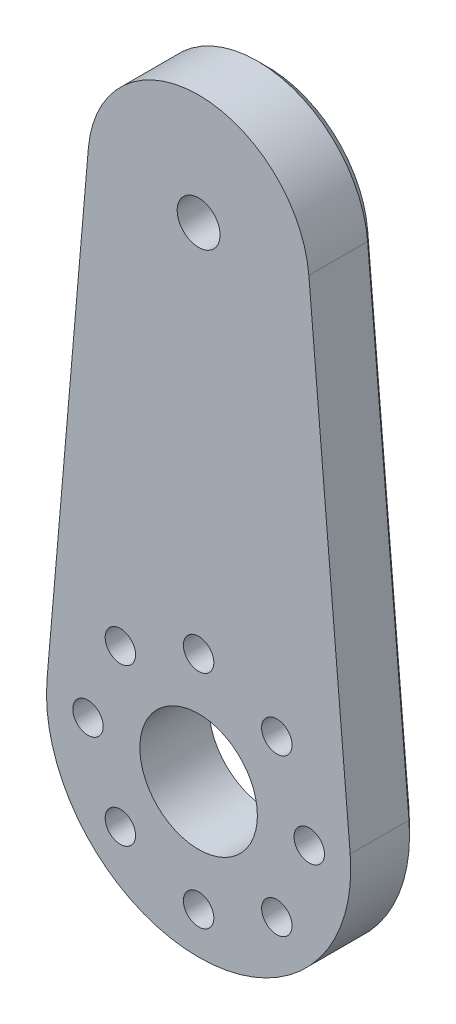
SolidWorks part; units mm, degrees
ref_plane "Front Plane" through (0, 0, 0) normal (0, 0, 1) x (1, 0, 0)
ref_plane "Top Plane" through (0, 0, 0) normal (0, 1, 0) x (1, 0, 0)
ref_plane "Right Plane" through (0, 0, 0) normal (1, 0, 0) x (0, 0, -1)
sketch "Sketch1" plane through (0, 0, 0) normal (0, 0, 1) x (1, 0, 0)
  line L0 (-23.0882, 16.319) -> (-26.0771, -18.4239)
  line L3 (-7.1471, 16.319) -> (-4.1581, -18.4239)
  line L4 (-15.1176, 0.8298) -> (-15.1176, 20.8298) construction
  line L5 (-14.7664, -19.3668) -> (49985.2336, -19.3668) construction
  circle A2 centre (-15.1176, 15.6332) radius 1.55
  circle A3 centre (-15.1176, -19.3668) radius 4.25
  arc A5 (-7.1471, 16.319) -> (-23.0882, 16.319) centre (-15.1176, 15.6332) ccw
  arc A6 (-26.0771, -18.4239) -> (-4.1581, -18.4239) centre (-15.1176, -19.3668) ccw
  circle A7 centre (-15.0314, -20.0888) radius 11 construction
  circle A8 centre (-7.1176, -19.3668) radius 1.1
  circle A9 centre (-9.4608, -25.0236) radius 1.1
  circle A10 centre (-15.1176, -27.3668) radius 1.1
  circle A11 centre (-20.7745, -25.0236) radius 1.1
  circle A12 centre (-23.1176, -19.3668) radius 1.1
  circle A13 centre (-20.7745, -13.7099) radius 1.1
  circle A14 centre (-15.1176, -11.3668) radius 1.1
  circle A15 centre (-9.4608, -13.7099) radius 1.1
  point P30 (-15.1176, -19.3668)
  dimension "D1" = 3.1
  dimension "D3" = 35
  dimension "D4" = 11
  dimension "D2" = 8
  dimension "D5" = 8.5
  dimension "D6" = 2.2
  dimension "D7" = 8
  dimension "D8" = 8
extrude "Boss-Extrude1" add sketch "Sketch1" along normal blind 5
sketch "Sketch2" plane through (0, 0, 5) normal (0, 0, 1) x (1, 0, 0)
  circle A0 centre (-15.1176, -19.3668) radius 11.5
  dimension "D1" = 23
extrude "Cut-Extrude1" [suppressed] cut sketch "Sketch2" against normal blind 1.75
sketch "Sketch3" plane through (0, 0, 0) normal (0, 0, 1) x (1, 0, 0)
  line L1 (-13.5299, 12.8832) -> (-11.9422, 15.6332)
  line L2 (-11.9422, 15.6332) -> (-13.5299, 18.3832)
  line L3 (-13.5299, 18.3832) -> (-16.7053, 18.3832)
  line L4 (-16.7053, 18.3832) -> (-18.2931, 15.6332)
  line L5 (-18.2931, 15.6332) -> (-16.7053, 12.8832)
  line L6 (-16.7053, 12.8832) -> (-13.5299, 12.8832)
  circle A0 centre (-15.1176, 15.6332) radius 2.75 construction
  dimension "D1" = 5.5
extrude "Cut-Extrude2" cut sketch "Sketch3" along normal blind 2
sketch "Sketch5" plane through (0, 0, 5) normal (0, 0, 1) x (1, 0, 0)
  circle A2 centre (-14.8897, 3.8764) radius 1.55
  circle A3 centre (-14.8897, 3.8764) radius 8
extrude "Boss-Extrude2" [suppressed] add sketch "Sketch5" along normal blind 3
fillet "Fillet1" [suppressed] radius 1
sketch "Sketch4" plane through (0, 0, 0) normal (0, 0, -1) x (-1, 0, 0)
  circle A0 centre (23.1176, -19.3668) radius 1.75
  circle A1 centre (20.7745, -25.0236) radius 1.75
  circle A2 centre (15.1176, -27.3668) radius 1.75
  circle A3 centre (9.4608, -25.0236) radius 1.75
  circle A4 centre (7.1176, -19.3668) radius 1.75
  circle A5 centre (9.4608, -13.7099) radius 1.75
  circle A6 centre (15.1176, -11.3668) radius 1.75
  circle A7 centre (20.7745, -13.7099) radius 1.75
  circle A10 centre (15.1176, -19.3668) radius 4.25 construction
  point P20 (15.1176, -19.3668)
  dimension "D1" = 3.5
extrude "Cut-Extrude3" cut sketch "Sketch4" against normal blind 2.25
chamfer "Chaflán1" distance 0.75 angle 45 4 edges at (-24.5827, -1.0525, 0) (-15.1176, -30.3668, 0) (-15.1176, 23.6332, 0) (-5.6526, -1.0525, 0)
